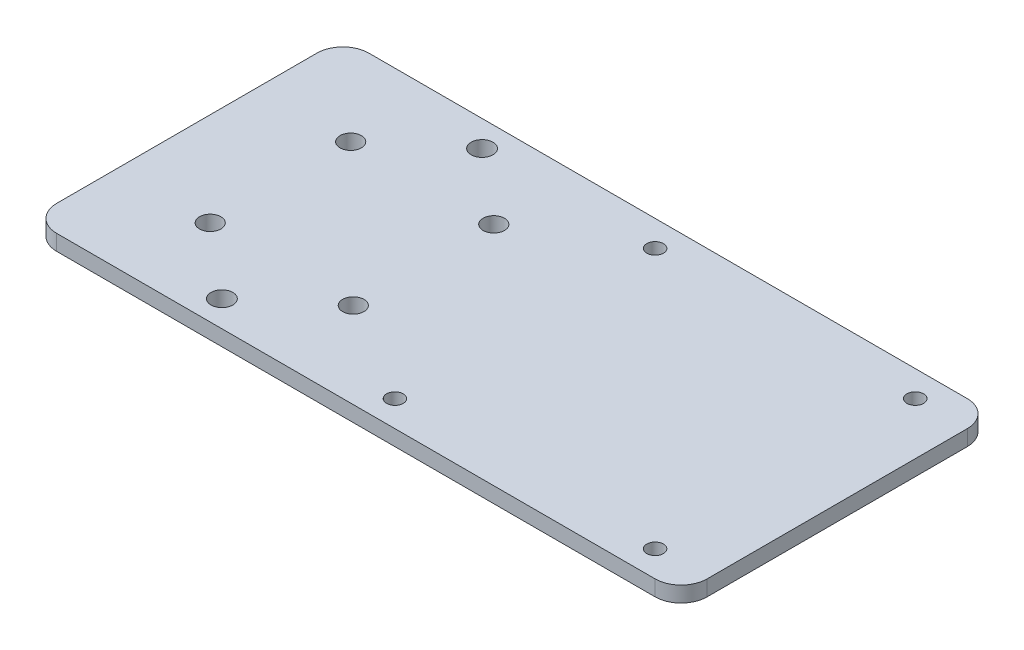
SolidWorks part; units mm, degrees
material "Thornel Mat VMA"
ref_plane "前视基准面" through (0, 0, 0) normal (0, 0, 1) x (1, 0, 0)
ref_plane "上视基准面" through (0, 0, 0) normal (0, 1, 0) x (1, 0, 0)
ref_plane "右视基准面" through (0, 0, 0) normal (1, 0, 0) x (0, 0, -1)
sketch "草图1" plane through (0, 0, 0) normal (0, 1, 0) x (1, 0, 0)
  line L0 (-21.4414, 42.5) -> (-21.4414, 102.5) construction
  line L1 (-246.4414, 42.5) -> (203.5586, 42.5)
  line L2 (-246.4414, 42.5) -> (-246.4414, 102.5)
  line L3 (-246.4414, 102.5) -> (203.5586, 102.5)
  line L4 (203.5586, 42.5) -> (203.5586, 102.5)
  line L5 (-61.4414, 102.5) -> (-61.4414, 168.5)
  line L6 (-61.4414, 168.5) -> (18.5586, 168.5)
  line L7 (18.5586, 168.5) -> (18.5586, 102.5)
  line L8 (-21.4414, 168.5) -> (-21.4414, 102.5) construction
  line L9 (-76.4414, 102.5) -> (-76.4414, 42.5)
  line L10 (-121.4414, 102.5) -> (-121.4414, 42.5)
  dimension "D1" = 450
  dimension "D2" = 60
  dimension "D3" = 66
  dimension "D4" = 80
  dimension "D5" = 15
  dimension "D6" = 45
extrude "凸台-拉伸1" add sketch "草图1" along normal blind 3 contours L10 L3 L2 L1
sketch "草图2" plane through (0, 3, 0) normal (0, 1, 0) x (1, 0, 0)
  line L0 (-228.4414, 59) -> (-228.4414, 86) construction
  line L1 (-200.9414, 59) -> (-200.9414, 86) construction
  line L2 (-228.4414, 86) -> (-200.9414, 86) construction
  line L3 (-130.9414, 47.5) -> (-130.9414, 97.5) construction
  line L4 (-214.6914, 86) -> (-214.6914, 102.5) construction
  line L5 (-246.4414, 102.5) -> (-121.4414, 102.5) construction
  line L6 (-246.4414, 72.5) -> (-121.4414, 72.5) construction
  line L7 (-246.4414, 42.5) -> (-246.4414, 102.5) construction
  line L9 (-228.4414, 72.5) -> (-130.9414, 72.5) construction
  line L12 (-121.4414, 102.5) -> (-121.4414, 42.5) construction
  circle A0 centre (-228.4414, 86) radius 2.05
  circle A1 centre (-228.4414, 59) radius 2.05
  circle A2 centre (-200.9414, 86) radius 2.05
  circle A3 centre (-200.9414, 59) radius 2.05
  circle A8 centre (-214.6914, 97.5) radius 2.1
  circle A9 centre (-214.6914, 47.5) radius 2.1
  point P3 (-228.4414, 72.5)
  point P8 (-200.9414, 72.5)
  point P13 (-130.9414, 72.5)
  dimension "D2" = 4.1
  dimension "D5" = 45.5
  dimension "D6" = 70
  dimension "D4" = 18
  dimension "D3" = 5
  dimension "D1" = 27
extrude "切除-拉伸1" cut sketch "草图2" against normal through all
sketch "草图3" plane through (0, 3, 0) normal (0, 1, 0) x (1, 0, 0)
  line L0 (-246.4414, 72.5) -> (-121.4414, 72.5) construction
  line L1 (-246.4414, 42.5) -> (-246.4414, 102.5) construction
  line L2 (-121.4414, 102.5) -> (-121.4414, 42.5) construction
  line L3 (-131.4414, 47.5) -> (-131.4414, 97.5) construction
  line L4 (-181.4414, 47.5) -> (-181.4414, 97.5) construction
  line L5 (-181.4414, 97.5) -> (-131.4414, 97.5) construction
  circle A0 centre (-181.4414, 97.5) radius 1.6
  circle A1 centre (-131.4414, 97.5) radius 1.6
  circle A2 centre (-131.4414, 47.5) radius 1.6
  circle A3 centre (-181.4414, 47.5) radius 1.6
  point P9 (-131.4414, 72.5)
  point P11 (-181.4414, 72.5)
  dimension "D4" = 3.2
  dimension "D5" = 3.2
  dimension "D1" = 50
  dimension "D3" = 10
extrude "切除-拉伸2" cut sketch "草图3" against normal through all
fillet "圆角1" radius 5 4 edges at (-246.4414, 1.5, -42.5) (-121.4414, 1.5, -42.5) (-121.4414, 1.5, -102.5) (-246.4414, 1.5, -102.5)
